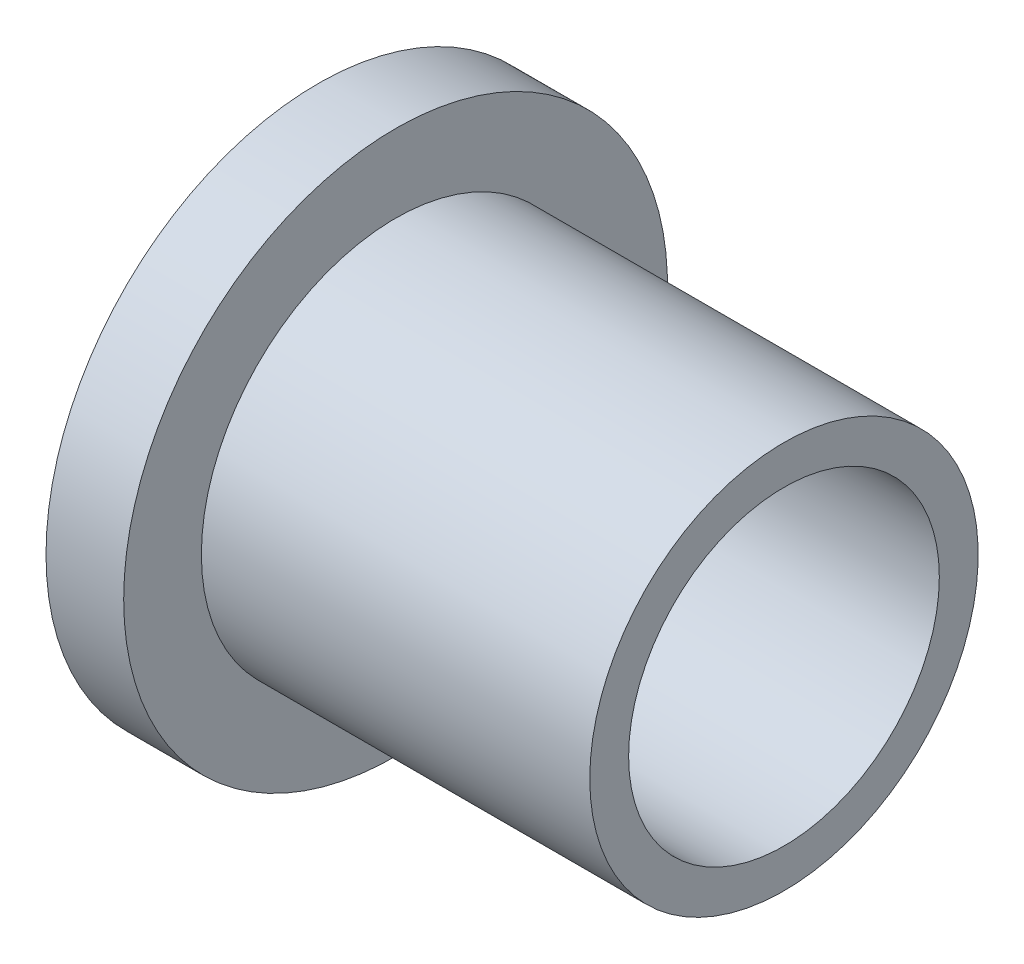
SolidWorks part; units mm, degrees
material "Leaded Commercial Bronze"
ref_plane "Front Plane" through (0, 0, 0) normal (0, 0, 1) x (1, 0, 0)
ref_plane "Top Plane" through (0, 0, 0) normal (0, 1, 0) x (1, 0, 0)
ref_plane "Right Plane" through (0, 0, 0) normal (1, 0, 0) x (0, 0, -1)
sketch "Sketch1" plane through (0, 0, 0) normal (1, 0, 0) x (0, 0, -1)
  circle A0 centre (0, 0) radius 7.9375
  circle A1 centre (0, 0) radius 6.35
  dimension "D1" = 15.875
  dimension "D2" = 12.7
extrude "Boss-Extrude1" add sketch "Sketch1" along normal blind 19.05
sketch "Sketch2" plane through (0, 0, 0) normal (-1, 0, 0) x (0, 0, 1)
  circle A0 centre (0, 0) radius 11.1125
  circle A1 centre (0, 0) radius 7.9375
  circle A2 centre (0, 0) radius 7.9375 construction
  dimension "D1" = 22.225
extrude "Boss-Extrude2" add sketch "Sketch2" against normal blind 3.175
